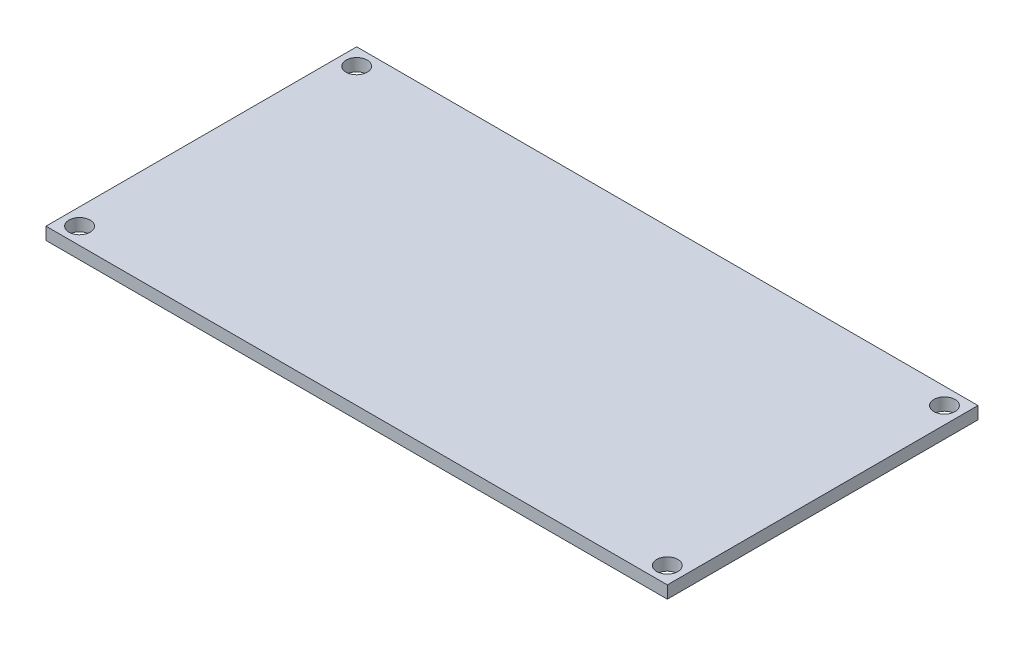
SolidWorks part; units mm, degrees
ref_plane "정면" through (0, 0, 0) normal (0, 0, 1) x (1, 0, 0)
ref_plane "윗면" through (0, 0, 0) normal (0, 1, 0) x (1, 0, 0)
ref_plane "우측면" through (0, 0, 0) normal (1, 0, 0) x (0, 0, -1)
sketch "스케치1" plane through (0, 0, 0) normal (0, 1, 0) x (1, 0, 0)
  line L1 (50, -25) -> (-50, -25)
  line L2 (50, -25) -> (50, 25)
  line L3 (50, 25) -> (-50, 25)
  line L4 (-50, -25) -> (-50, 25)
  line L5 (50, -25) -> (-50, 25) construction
  line L6 (50, 25) -> (-50, -25) construction
  point P0 (0, 0)
  dimension "D1" = 100
  dimension "D2" = 50
extrude "보스-돌출1" add sketch "스케치1" along normal blind 2
sketch "스케치2" plane through (0, 2, 0) normal (0, 1, 0) x (1, 0, 0)
  line L0 (50, 0) -> (0, 0) construction
  line L1 (50, -25) -> (50, 25) construction
  line L2 (0, 0) -> (0, 25) construction
  line L3 (50, 25) -> (-50, 25) construction
  line L4 (50, 22.3) -> (47.3, 22.3) construction
  line L5 (47.3, 22.3) -> (47.3, 25) construction
  circle A0 centre (47.3, 22.3) radius 1.7
  circle A1 centre (47.3, -22.3) radius 1.7
  circle A2 centre (-47.3, -22.3) radius 1.7
  circle A3 centre (-47.3, 22.3) radius 1.7
  dimension "D1" = 3.4
  dimension "D2" = 1
extrude "컷-돌출1" cut sketch "스케치2" against normal through all
